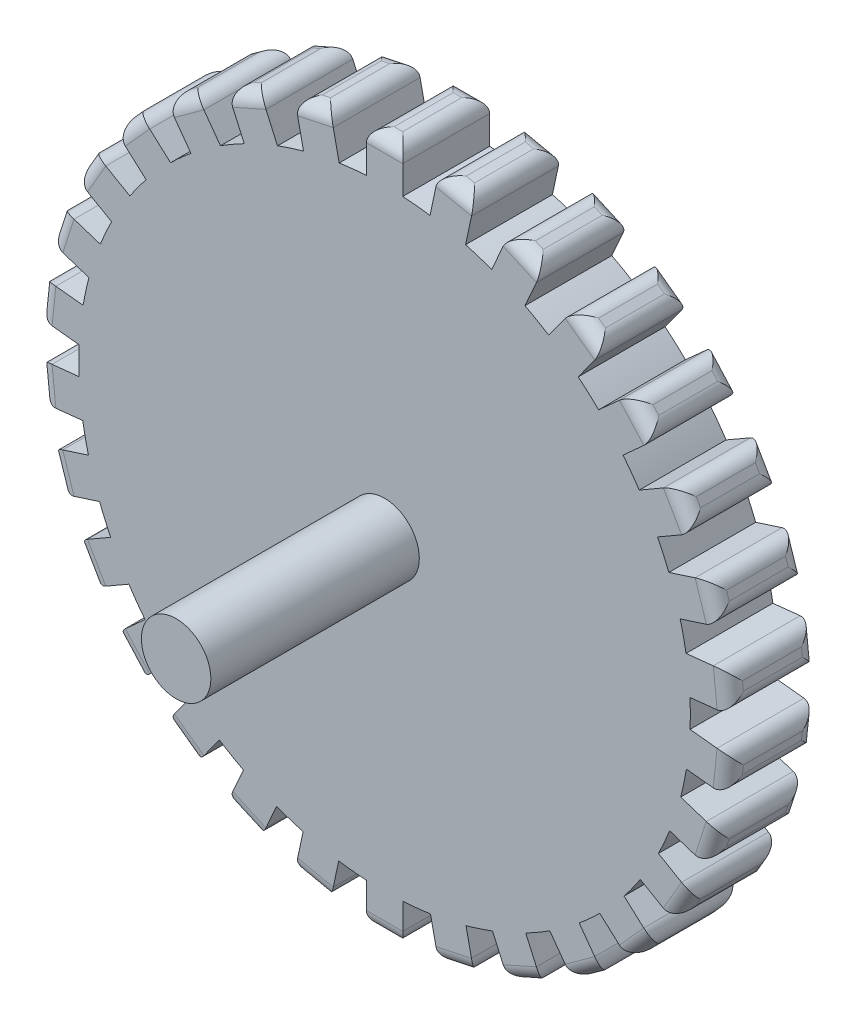
SolidWorks part; units mm, degrees
ref_plane "Front Plane" through (0, 0, 0) normal (0, 0, 1) x (1, 0, 0)
ref_plane "Top Plane" through (0, 0, 0) normal (0, 1, 0) x (1, 0, 0)
ref_plane "Right Plane" through (0, 0, 0) normal (1, 0, 0) x (0, 0, -1)
sketch "Sketch1" plane through (0, 0, 0) normal (0, 0, 1) x (1, 0, 0)
  circle A0 centre (0, 0) radius 88
extrude "Boss-Extrude3" add sketch "Sketch1" along normal blind 25
sketch "Sketch4" plane through (0, 0, 25) normal (0, 0, 1) x (1, 0, 0)
  line L0 (0, 88) -> (0, 100) construction
  line L1 (5.236, 100) -> (-5.236, 100)
  line L2 (-5.236, 100) -> (-5.236, 86.6488)
  line L3 (-5.236, 86.6488) -> (5.236, 86.6488)
  line L4 (5.236, 86.6488) -> (5.236, 100)
  circle A0 centre (0, 0) radius 88 construction
  point P9 (0, 100)
extrude "Boss-Extrude4" add sketch "Sketch4" against normal blind 25
fillet "Fillet2" radius 4 4 edges at (-5.236, 100, 12.5) (0, 100, 25) (0, 100, 0) (5.236, 100, 12.5)
pattern_circular "CirPattern1" count 30 over 360 about axis through (0, 0.3177, 0) along (0, 0, 1) of "Fillet2", "Boss-Extrude4"
ref_plane "Plane1" through (-5.236, 96, 25) normal (-1, 0, 0) x (0, 0, 1)
sketch "Sketch6" plane through (0, 0, 25) normal (0, 0, 1) x (1, 0, 0)
  circle A0 centre (0, 0) radius 10
extrude "Boss-Extrude5" add sketch "Sketch6" along normal blind 60
sketch "Sketch7" plane through (0, 0, 0) normal (0, 0, -1) x (-1, 0, 0)
  circle A0 centre (0, 0) radius 10
extrude "Boss-Extrude6" add sketch "Sketch7" along normal blind 10
